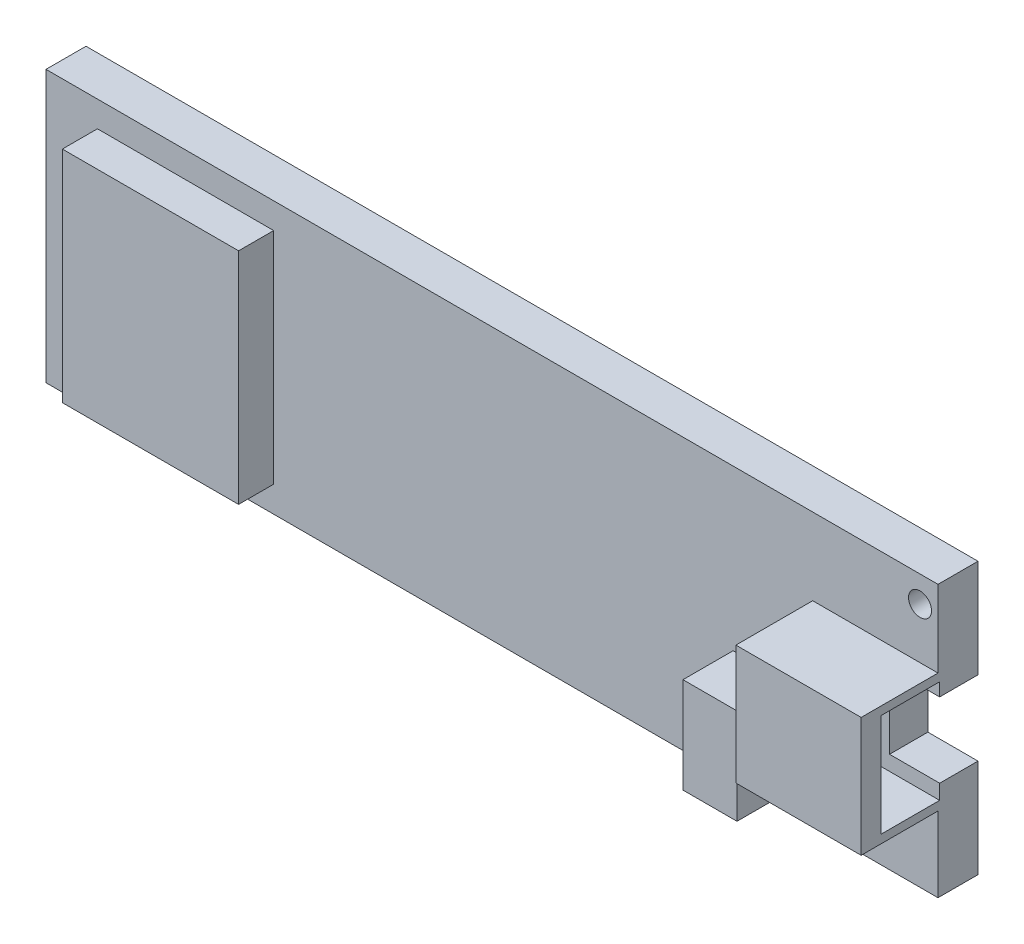
SolidWorks part; units mm, degrees
ref_plane "Front Plane" through (0, 0, 0) normal (0, 0, 1) x (1, 0, 0)
ref_plane "Top Plane" through (0, 0, 0) normal (0, 1, 0) x (1, 0, 0)
ref_plane "Right Plane" through (0, 0, 0) normal (1, 0, 0) x (0, 0, -1)
sketch "Sketch1" plane through (0, 0, 0) normal (0, 0, 1) x (1, 0, 0)
  line L1 (53.4, -16.25) -> (-53.4, -16.25)
  line L2 (53.4, -16.25) -> (53.4, 16.25)
  line L3 (53.4, 16.25) -> (-53.4, 16.25)
  line L4 (-53.4, -16.25) -> (-53.4, 16.25)
  line L5 (53.4, -16.25) -> (-53.4, 16.25) construction
  line L6 (53.4, 16.25) -> (-53.4, -16.25) construction
  point P0 (0, 0)
  dimension "D1" = 106.8
  dimension "D2" = 32.5
extrude "Boss-Extrude1" add sketch "Sketch1" along normal blind 4.79
sketch "Sketch2" plane through (0, 0, 4.79) normal (0, 0, 1) x (1, 0, 0)
  line L0 (0, 0) -> (-58.1309, 0) construction
  line L1 (0, 0) -> (56.8643, 0) construction
  line L2 (-47.24, 24.7452) -> (-47.24, -26.8262) construction
  line L3 (39.7643, 24.7452) -> (39.7643, -24.1119) construction
  line L4 (-53.4, 16.25) -> (-53.4, -16.25) construction
  line L5 (-47.24, 13.1643) -> (-26.14, -13.1357) construction
  line L6 (-47.24, 13.1643) -> (-26.14, 13.1643)
  line L7 (-47.24, 13.1643) -> (-47.24, -13.1357)
  line L8 (-47.24, -13.1357) -> (-26.14, -13.1357)
  line L9 (-26.14, 13.1643) -> (-26.14, -13.1357)
  line L10 (-26.14, 13.1643) -> (-47.24, -13.1357) construction
  dimension "D1" = 6.16
  dimension "D2" = 21.1
  dimension "D3" = 26.3
extrude "Boss-Extrude2" add sketch "Sketch2" along normal blind 4.2
sketch "Sketch3" plane through (0, 0, 4.79) normal (0, 0, 1) x (1, 0, 0)
  line L0 (53.4, 7.05) -> (38.4, 7.05)
  line L1 (53.4, -16.25) -> (53.4, 16.25) construction
  line L2 (53.4, -7.25) -> (38.4, -7.25)
  line L3 (38.4, 7.05) -> (38.4, -7.25)
  line L4 (-53.4, -16.25) -> (53.4, -16.25) construction
  line L5 (53.4, 16.25) -> (-53.4, 16.25) construction
  line L6 (53.4, 7.05) -> (53.4, -7.25)
  dimension "D1" = 15
  dimension "D2" = 23.3
  dimension "D3" = 23.5
extrude "Boss-Extrude3" add sketch "Sketch3" along normal blind 9.2
sketch "Sketch4" plane through (0, 0, 4.79) normal (0, 0, 1) x (1, 0, 0)
  line L0 (32.1, 23.0262) -> (32.1, -32.8881) construction
  line L1 (18.3214, -8.63) -> (61.8404, -8.63) construction
  line L2 (53.4, 7.05) -> (53.4, 16.25) construction
  line L3 (-53.4, -16.25) -> (53.4, -16.25) construction
  line L5 (28.865, -2.905) -> (35.335, -2.905)
  line L6 (28.865, -2.905) -> (28.865, -14.355)
  line L7 (28.865, -14.355) -> (35.335, -14.355)
  line L8 (35.335, -2.905) -> (35.335, -14.355)
  line L9 (28.865, -2.905) -> (35.335, -14.355) construction
  line L10 (28.865, -14.355) -> (35.335, -2.905) construction
  point P8 (32.1, -8.63)
  dimension "D1" = 21.3
  dimension "D2" = 7.62
  dimension "D3" = 11.45
  dimension "D4" = 6.47
extrude "Boss-Extrude4" add sketch "Sketch4" along normal blind 6
sketch "Sketch5" plane through (0, 0, 4.79) normal (0, 0, 1) x (1, 0, 0)
  line L0 (53.4, 7.05) -> (53.4, 16.25) construction
  line L1 (53.4, 16.25) -> (-53.4, 16.25) construction
  circle A0 centre (51.25, 13.12) radius 1.375
  dimension "D3" = 2.75
  dimension "D1" = 2.15
  dimension "D2" = 3.13
extrude "Cut-Extrude1" cut sketch "Sketch5" against normal through all
sketch "Sketch6" plane through (53.4, 0, 0) normal (1, 0, 0) x (0, 0, -1)
  line L0 (-11.59, 6.05) -> (-11.59, -6.25)
  line L1 (-11.59, 6.05) -> (-4.59, 6.05)
  line L2 (-11.59, -6.25) -> (-4.59, -6.25)
  line L3 (-13.99, -7.25) -> (-13.99, 7.05) construction
  line L4 (-13.99, -7.25) -> (-4.79, -7.25) construction
  line L5 (-13.99, 7.05) -> (-4.79, 7.05) construction
  line L6 (-4.59, 6.05) -> (-4.59, -6.25)
  dimension "D1" = 2.4
  dimension "D2" = 1
  dimension "D3" = 1
  dimension "D4" = 7
extrude "Cut-Extrude2" cut sketch "Sketch6" against normal blind 12
sketch "Sketch7" plane through (53.4, 0, 0) normal (1, 0, 0) x (0, 0, -1)
  line L0 (-4.59, -6.25) -> (-4.59, 6.05) construction
  line L1 (0.3271, -4.4716) -> (-4.59, -4.4716)
  line L2 (0.3271, -4.4716) -> (0.3271, 4.4716)
  line L3 (0.3271, 4.4716) -> (-4.59, 4.4716)
  line L4 (-4.59, -4.4716) -> (-4.59, 4.4716)
  line L5 (0.3271, -4.4716) -> (-4.59, 4.4716) construction
  line L6 (0.3271, 4.4716) -> (-4.59, -4.4716) construction
  point P0 (-2.1315, 0)
extrude "Cut-Extrude3" cut sketch "Sketch7" against normal blind 6
